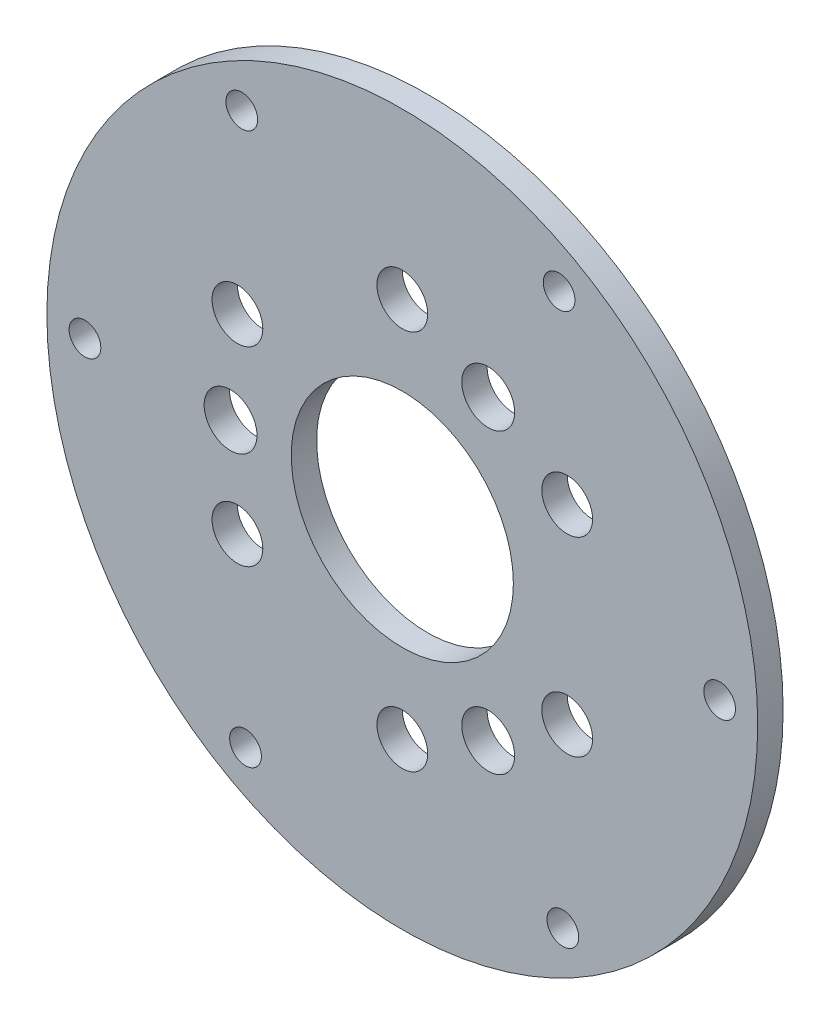
SolidWorks part; units mm, degrees
ref_plane "前视基准面" through (0, 0, 0) normal (0, 0, 1) x (1, 0, 0)
ref_plane "上视基准面" through (0, 0, 0) normal (0, 1, 0) x (1, 0, 0)
ref_plane "右视基准面" through (0, 0, 0) normal (1, 0, 0) x (0, 0, -1)
sketch "草图1" plane through (0, 0, 0) normal (0, 0, 1) x (1, 0, 0)
  line L0 (0, 0) -> (0, -3.3498) construction
  line L1 (0, 0) -> (14.2454, 25.0675) construction
  line L2 (14.2454, 25.0675) -> (12.3519, 21.7355) construction
  circle A0 centre (0, 0) radius 15 construction
  circle A1 centre (0, 0) radius 13.53 construction
  circle A2 centre (0, -15) radius 2
  circle A3 centre (-12.9904, -7.5) radius 2
  circle A4 centre (-12.9904, 7.5) radius 2
  circle A5 centre (0, 15) radius 2
  circle A6 centre (12.9904, 7.5) radius 2
  circle A7 centre (12.9904, -7.5) radius 2
  circle A8 centre (-13.53, 0) radius 2.08
  circle A9 centre (6.765, 11.7173) radius 2.08
  circle A10 centre (6.765, -11.7173) radius 2.08
  circle A11 centre (0, 0) radius 8.75
  circle A14 centre (0, 0) radius 25 construction
  circle A23 centre (0, 0) radius 28
  circle A30 centre (12.3519, 21.7355) radius 1.25
  circle A31 centre (24.9994, 0.1707) radius 1.25
  circle A32 centre (12.6476, -21.5648) radius 1.25
  circle A33 centre (-12.3519, -21.7355) radius 1.25
  circle A34 centre (-24.9994, -0.1707) radius 1.25
  circle A35 centre (-12.6476, 21.5648) radius 1.25
  point P51 (-13, 22.5167)
  point P52 (-13, -22.5167)
  point P53 (26, 0)
  point P54 (-13, 22.5167)
  dimension "D1" = 6
extrude "凸台-拉伸1" add sketch "草图1" along normal blind 2
sketch "草图2" plane through (0, 0, 2) normal (0, 0, 1) x (1, 0, 0)
  circle A0 centre (-12.6476, 21.5648) radius 1.5
  circle A1 centre (12.3519, 21.7355) radius 1.5
  circle A2 centre (24.9994, 0.1707) radius 1.5
  circle A3 centre (12.6476, -21.5648) radius 1.5
  circle A4 centre (-12.3519, -21.7355) radius 1.5
  circle A5 centre (-24.9994, -0.1707) radius 1.5
  dimension "D1" = 6
sketch "草图3" plane through (0, 0, 0) normal (0, 0, -1) x (-1, 0, 0)
  circle A0 centre (12.6476, 21.5648) radius 1.5
  circle A1 centre (24.9994, -0.1707) radius 1.5
  circle A2 centre (12.3519, -21.7355) radius 1.5
  circle A3 centre (-12.6476, -21.5648) radius 1.5
  circle A4 centre (-24.9994, 0.1707) radius 1.5
  circle A5 centre (-12.3519, 21.7355) radius 1.5
  dimension "D1" = 6
